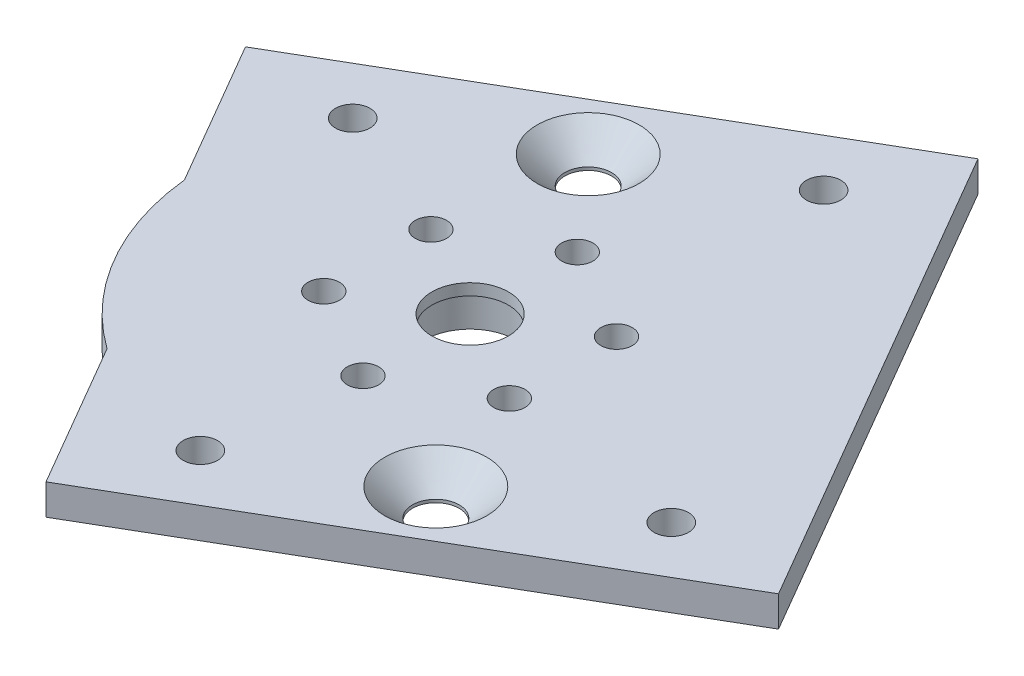
SolidWorks part; units mm, degrees
material "6061 合金"
ref_plane "前视基准面" through (0, 0, 0) normal (0, 0, 1) x (1, 0, 0)
ref_plane "上视基准面" through (0, 0, 0) normal (0, 1, 0) x (1, 0, 0)
ref_plane "右视基准面" through (0, 0, 0) normal (1, 0, 0) x (0, 0, -1)
sketch "草图1" plane through (0, 0, 0) normal (0, 1, 0) x (1, 0, 0)
  circle A0 centre (0, 0) radius 34
  circle A1 centre (0, 0) radius 14 construction
  circle A2 centre (0, 14) radius 2.05
  circle A3 centre (12.1244, 7) radius 2.05
  circle A4 centre (12.1244, -7) radius 2.05
  circle A5 centre (0, -14) radius 2.05
  circle A6 centre (-12.1244, -7) radius 2.05
  circle A7 centre (-12.1244, 7) radius 2.05
  circle A10 centre (0, 0) radius 6
  point P23 (0, 0)
  dimension "D1" = 68
  dimension "D2" = 28
  dimension "D3" = 4.1
  dimension "D5" = 12
  dimension "D4" = 6
extrude "凸台-拉伸1" add sketch "草图1" along normal blind 4
ref_plane "基准面1" through (0, 4, 0) normal (0, 1, 0) x (1, 0, 0)
ref_plane "基准面2" through (0, 0, 0) normal (0, -1, 0) x (-1, 0, 0)
sketch "草图5" plane through (0, 4, 0) normal (0, 1, 0) x (1, 0, 0)
  circle A0 centre (0, 0) radius 5
  circle A1 centre (0, 0) radius 6.5
  dimension "D1" = 10
  dimension "D2" = 13
extrude "凸台-拉伸4" add sketch "草图5" against normal blind 1.5
sketch "草图6" plane through (0, 0, 0) normal (0, -1, 0) x (-1, 0, 0)
  circle A0 centre (0, 0) radius 6
  circle A1 centre (0, 0) radius 7
  dimension "D1" = 14
  dimension "D2" = 12
extrude "凸台-拉伸5" add sketch "草图6" along normal blind 2
ref_plane "基准面3" through (0, 4, 0) normal (0, 1, 0) x (1, 0, 0)
sketch "草图8" plane through (0, 4, 0) normal (0, 1, 0) x (1, 0, 0)
  line L0 (51.8096, -11.5226) -> (15.6239, 50.7237)
  line L1 (51.8096, -11.5226) -> (-8.7076, -46.7031)
  line L2 (15.6239, 50.7237) -> (-44.8933, 15.5432)
  line L3 (-8.7076, -46.7031) -> (-44.8933, 15.5432)
  circle A0 centre (0, 0) radius 34
extrude "凸台-拉伸6" add sketch "草图8" against normal blind 4 contours A0 L3 L1 L0 L2
ref_plane "基准面4" through (0, 0, 0) normal (0, -1, 0) x (-1, 0, 0)
sketch "草图9" plane through (0, 0, 0) normal (0, -1, 0) x (-1, 0, 0)
  line L0 (-9.3405, 36.6607) -> (-36.4797, -10.024) construction
  line L1 (-36.4797, -10.024) -> (2.4242, -32.6401) construction
  line L2 (-9.3405, 36.6607) -> (29.5635, 14.0446) construction
  line L3 (10.1115, 25.3527) -> (-17.0278, -21.332) construction
  line L4 (29.5635, 14.0446) -> (2.4242, -32.6401) construction
  line L5 (-36.731, -10.4563) -> (2.1729, -33.0723) construction
  line L6 (2.1729, -33.0723) -> (2.4242, -32.6401) construction
  line L7 (-22.9101, 13.3183) -> (15.9938, -9.2977) construction
  circle A0 centre (-9.3405, 36.6607) radius 2.25
  circle A1 centre (-36.4797, -10.024) radius 2.25
  circle A2 centre (29.5635, 14.0446) radius 2.25
  circle A3 centre (2.4242, -32.6401) radius 2.25
  circle A4 centre (10.1115, 25.3527) radius 3.05
  circle A5 centre (-17.0278, -21.332) radius 3.05
  circle A6 centre (-36.731, -10.4563) radius 2.25
  circle A7 centre (-9.0892, 37.093) radius 2.25
  circle A8 centre (-17.279, -21.7643) radius 3.05
  circle A9 centre (2.1729, -33.0723) radius 2.25
  circle A10 centre (29.8147, 14.4769) radius 2.25
  circle A11 centre (10.3628, 25.7849) radius 3.05
  point P29 (15.2066, -11.2043)
  point P30 (0, 0)
  dimension "D1" = 4.5
  dimension "D2" = 6.1
  dimension "D3" = 4.5
  dimension "D4" = 4.5
  dimension "D5" = 6.1
  dimension "D6" = 4.5
  dimension "D8" = 4.5
  dimension "D10" = 4.5
  dimension "D12" = 4.5
  dimension "D13" = 6.1
  dimension "D7" = 0.5
  dimension "D9" = 0.5
  dimension "D11" = 0.5
extrude "切除-拉伸1" cut sketch "草图9" against normal blind 10 contours A1 A6 | A1 A6 | A5 A8 | A5 A8 | A3 A9 | A3 A9 | A10 A2 | A11 A4 | A0 A7 | A11 A4 | A10 A2
chamfer "倒角2" distance 3.6 angle 45 2 edges at (-10.3628, 4, -22.7349) (17.279, 4, 24.8143)
ref_plane "基准面5" through (0, -2, 0) normal (0, -1, 0) x (-1, 0, 0)
sketch "草图10" plane through (0, -2, 0) normal (0, -1, 0) x (-1, 0, 0)
  circle A0 centre (0, 0) radius 6.05
  dimension "D1" = 12.1
extrude "切除-拉伸3" cut sketch "草图10" against normal up to surface (4.5 mm away) up to face at (0, 2.5, 5)
